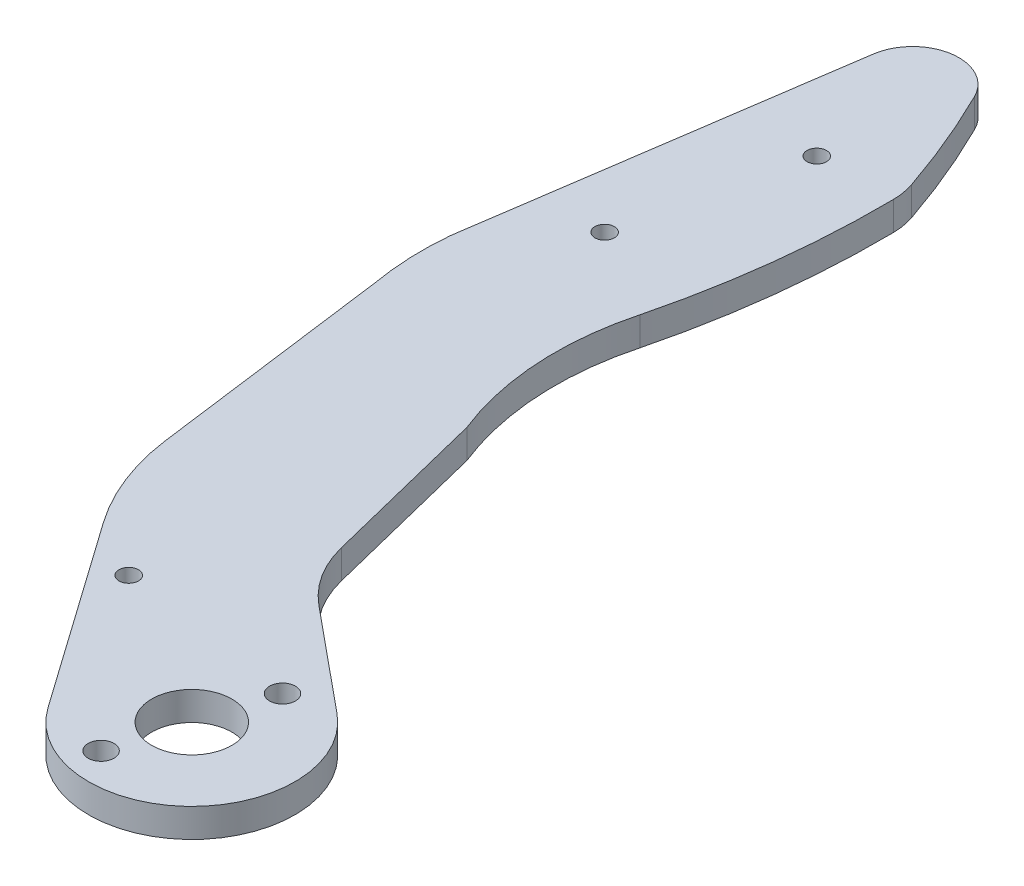
SolidWorks part; units mm, degrees
ref_plane "Front Plane" through (0, 0, 0) normal (0, 0, 1) x (1, 0, 0)
ref_plane "Top Plane" through (0, 0, 0) normal (0, 1, 0) x (1, 0, 0)
ref_plane "Right Plane" through (0, 0, 0) normal (1, 0, 0) x (0, 0, -1)
sketch "Sketch1" plane through (0, 0, 0) normal (0, 1, 0) x (1, 0, 0)
  line L42 (11.4465, 13.8917) -> (-6.607, 28.7674)
  line L43 (-13.2989, 39.3817) -> (-20.5302, 68.4972)
  line L44 (-41.4826, 160.3656) -> (-50.9327, 96.0562)
  line L45 (-50.3835, 82.3644) -> (-44.8193, 40.2497)
  line L46 (-37.8507, 22.4331) -> (-14.709, -10.3752)
  arc A148 (-22.4566, 100.5997) -> (-20.5302, 68.4972) centre (26.9938, 87.458) ccw
  arc A149 (-22.4566, 100.5997) -> (-17.768, 140.1479) centre (-171.2572, 138.2924) ccw
  arc A150 (-17.768, 140.1479) -> (-18.4178, 143.9365) centre (-30, 140) ccw
  arc A151 (-18.4178, 143.9365) -> (-26.2563, 162.7822) centre (-163.7532, 94.5401) ccw
  arc A152 (-26.2563, 162.7822) -> (-41.4826, 160.3656) centre (-33.4913, 159.1913) ccw
  arc A153 (-50.9327, 96.0562) -> (-50.3835, 82.3644) centre (0.0072, 91.2427) ccw
  circle A154 centre (0, 0) radius 7
  arc A155 (11.4465, 13.8917) -> (-14.709, -10.3752) centre (0, 0) cw
  arc A156 (-6.607, 28.7674) -> (-13.2989, 39.3817) centre (6.1114, 44.2025) cw
  arc A157 (-44.8193, 40.2497) -> (-37.8507, 22.4331) centre (-5.1639, 45.489) ccw
  circle A158 centre (-27.6733, 16.679) radius 1.7
  point P7 (-11.7063, 32.9691)
  point P11 (-43.529, 30.4833)
  dimension "D3" = 65
  dimension "D4" = 14
  dimension "D5" = 11
  dimension "D8" = 20
  dimension "D10" = 40
  dimension "D11" = 3.4
  dimension "D1" = 140
  dimension "D2" = 30
  dimension "D6" = 50
  dimension "D7" = 30
  dimension "D9" = 30
  dimension "D12" = 5
  dimension "D13" = 30
extrude "Boss-Extrude2" add sketch "Sketch1" along normal blind 5
sketch "Sketch2" plane through (0, 5, 0) normal (0, 1, 0) x (1, 0, 0)
  line L0 (11.4465, 13.8917) -> (-6.607, 28.7674) construction
  point P0 (8.4963, 16.3225)
sketch "Sketch3" plane through (0, 5, 0) normal (0, 1, 0) x (1, 0, 0)
  circle A0 centre (-31, 140) radius 1.7
  circle A1 centre (-38, 110) radius 1.7
  dimension "D1" = 3.4
  dimension "D2" = 3.4
  dimension "D3" = 30
  dimension "D4" = 110
  dimension "D5" = 38
  dimension "D6" = 7
extrude "Cut-Extrude1" cut sketch "Sketch3" against normal up to next
sketch "Sketch6" plane through (0, 5, 0) normal (0, 1, 0) x (1, 0, 0)
  point P0 (3.5854, 12.2355)
  point P1 (-3.5854, -12.2355)
hole_wizard "M4 Clearance Hole1" positions "3DSketch1" profile "Sketch7" hole size "M4" standard "ISO"
sketch3d "3DSketch1"
  point P0 (-3.5854, 5, 12.2355)
  point P3 (3.5854, 5, -12.2355)
sketch "Sketch7" plane through (-3.5854, 5, 12.2355) normal (1, 0, 0) x (0, 0, 1)
  line L0 (0, 0) -> (0, 11.4519)
  line L1 (0, 11.4519) -> (2.25, 10.1)
  line L2 (2.25, 10.1) -> (2.25, 0)
  line L5 (2.25, 0) -> (0, 0)
  line L10 (0, 11.4519) -> (-2.25, 10.1) construction
  line L11 (0, -6.35) -> (0, 107.95) construction
  dimension "Hole Dia." = 4.5
  dimension "Hole Depth" = 10.1
  dimension "Drill Angle" = 118
